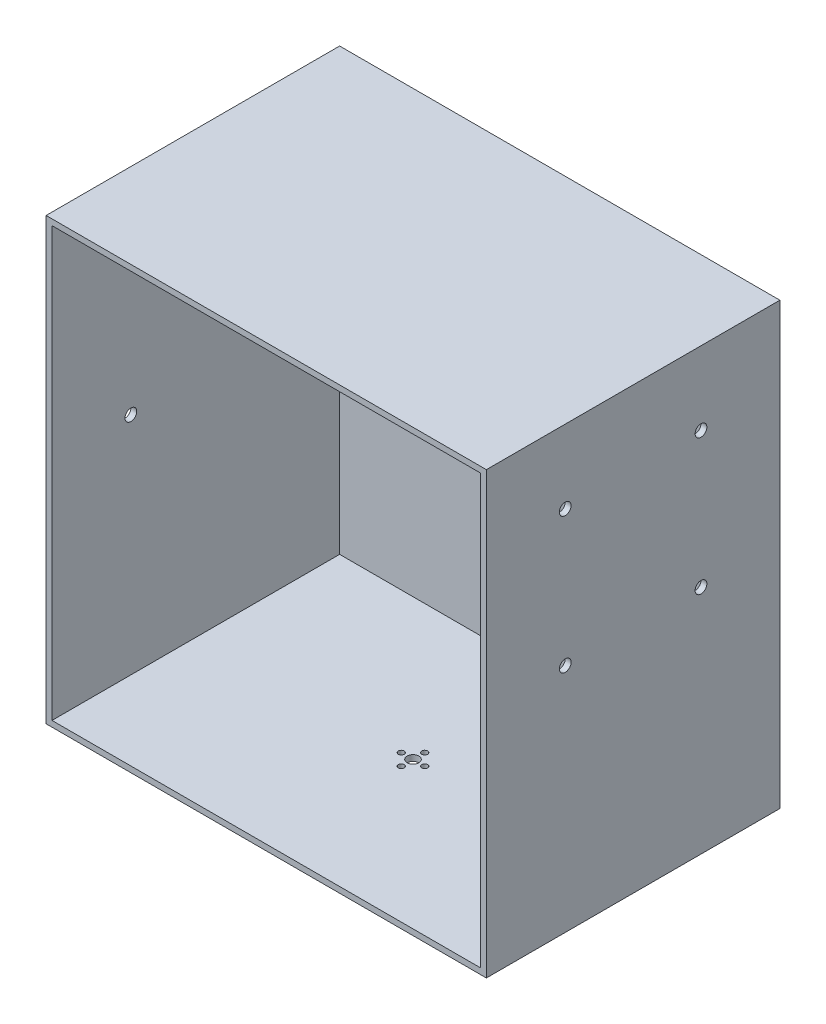
SolidWorks part; units mm, degrees
ref_plane "Ön Düzlem" through (0, 0, 0) normal (0, 0, 1) x (1, 0, 0)
ref_plane "Üst Düzlem" through (0, 0, 0) normal (0, 1, 0) x (1, 0, 0)
ref_plane "Sağ Düzlem" through (0, 0, 0) normal (1, 0, 0) x (0, 0, -1)
sketch "Çizim1" plane through (0, 0, 0) normal (0, 0, 1) x (1, 0, 0)
  line L1 (0, 0) -> (-300, 0)
  line L2 (0, 0) -> (0, 300)
  line L3 (0, 300) -> (-300, 300)
  line L4 (-300, 0) -> (-300, 300)
  dimension "D1" = 300
  dimension "D2" = 300
extrude "Yükseklik-Ekstrüzyon1" add sketch "Çizim1" along normal blind 200
shell "İç Boşaltma1" thickness 4
ref_plane "Düzlem1" through (-150, 0, 0) normal (1, 0, 0) x (0, 0, -1)
sketch "Çizim2" plane through (-300, 0, 0) normal (-1, 0, 0) x (0, 0, 1)
  circle A0 centre (146.25, 250) radius 4
  circle A1 centre (53.75, 250) radius 4
  circle A2 centre (146.25, 157.5) radius 4
  circle A3 centre (53.75, 157.5) radius 4
  dimension "D5" = 8
  dimension "D6" = 8
  dimension "D7" = 8
  dimension "D8" = 8
  dimension "D3" = 92.5
  dimension "D4" = 92.5
  dimension "D1" = 92.5
  dimension "D2" = 92.5
extrude "Kes-Ekstrüzyon1" cut sketch "Çizim2" against normal up to next
mirror "Aynalama1" about plane through (-150, 0, 0) normal (1, 0, 0) of "Kes-Ekstrüzyon1"
sketch "Çizim3" plane through (0, 0, 0) normal (0, -1, 0) x (1, 0, 0)
  line L0 (-300, 200) -> (0, 200) construction
  line L1 (-300, 200) -> (-300, 0) construction
  line L2 (-150, 100) -> (-157.7911, 100) construction
  line L3 (-150, 100) -> (-150, 102.8886) construction
  circle A0 centre (-150, 100) radius 4
  circle A1 centre (-150, 108) radius 2
  circle A2 centre (-158, 100) radius 2
  circle A3 centre (-150, 92) radius 2
  circle A4 centre (-142, 100) radius 2
  dimension "D1" = 100
  dimension "D2" = 150
  dimension "D3" = 8
  dimension "D4" = 4
  dimension "D5" = 8
  dimension "D6" = 4
  dimension "D7" = 8
extrude "Kes-Ekstrüzyon2" cut sketch "Çizim3" against normal up to next
